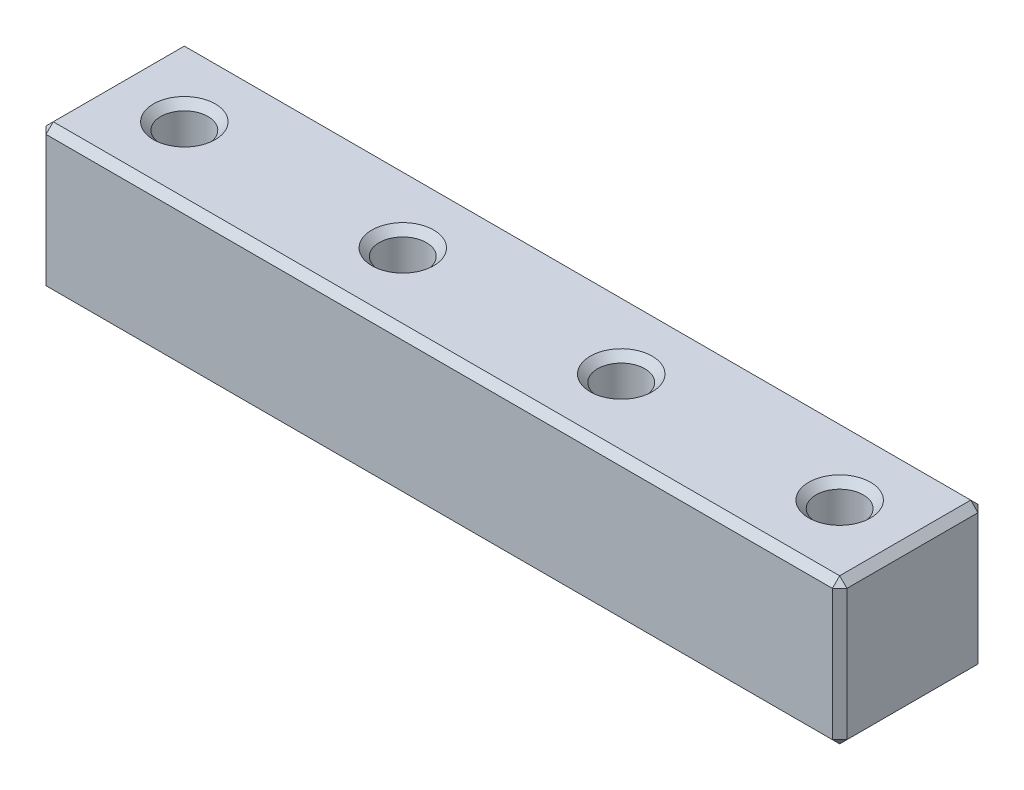
SolidWorks part; units mm, degrees
material "HDPE, Black"
ref_plane "Front Plane" through (0, 0, 0) normal (0, 0, 1) x (1, 0, 0)
ref_plane "Top Plane" through (0, 0, 0) normal (0, 1, 0) x (1, 0, 0)
ref_plane "Right Plane" through (0, 0, 0) normal (1, 0, 0) x (0, 0, -1)
sketch "Sketch1" plane through (0, 0, 0) normal (0, 1, 0) x (1, 0, 0)
  line L0 (-45, 0) -> (-15, 0) construction
  line L1 (-55, -10) -> (55, -10)
  line L2 (-55, -10) -> (-55, 10)
  line L3 (-55, 10) -> (55, 10)
  line L4 (55, -10) -> (55, 10)
  line L5 (-55, -10) -> (55, 10) construction
  line L6 (-55, 10) -> (55, -10) construction
  line L7 (-15, 0) -> (15, 0) construction
  line L9 (15, 0) -> (45, 0) construction
  circle A0 centre (-45, 0) radius 3.25
  circle A1 centre (-15, 0) radius 3.25
  circle A3 centre (15, 0) radius 3.25
  circle A4 centre (45, 0) radius 3.25
  point P0 (0, 0)
  point P17 (0, 0)
  dimension "D4" = 6.5
  dimension "D1" = 20
  dimension "D2" = 110
  dimension "D3" = 30
extrude "Boss-Extrude1" add sketch "Sketch1" along normal blind 20
chamfer "Chamfer1" distance 1 angle 45 20 edges at (55, 20, 0) (55, 0, 0) (55, 10, -10) (0, 20, -10) (0, 0, -10) (-55, 10, -10) (-55, 20, 0) (-55, 0, 0) (-55, 10, 10) (0, 20, 10) (55, 10, 10) (0, 0, 10) (45, 0, 3.25) (45, 20, 3.25) (15, 0, 3.25) (15, 20, 3.25) (-15, 0, 3.25) (-15, 20, 3.25) (-45, 0, 3.25) (-45, 20, 3.25)
